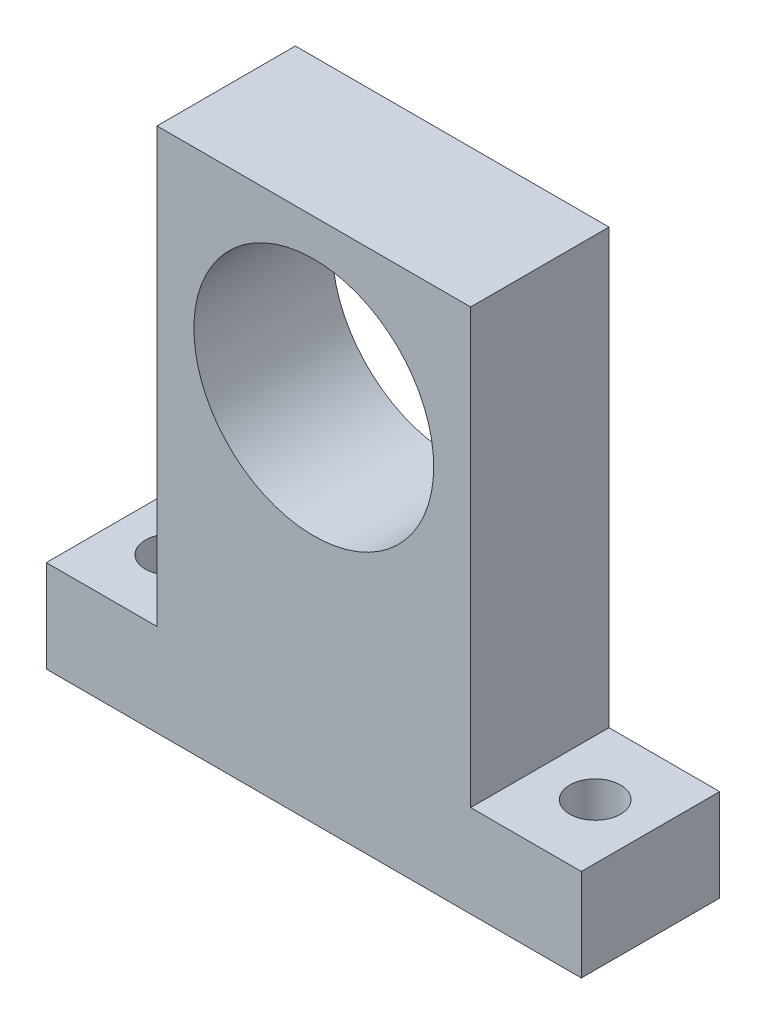
SolidWorks part; units mm, degrees
ref_plane "前视基准面" through (0, 0, 0) normal (0, 0, 1) x (1, 0, 0)
ref_plane "上视基准面" through (0, 0, 0) normal (0, 1, 0) x (1, 0, 0)
ref_plane "右视基准面" through (0, 0, 0) normal (1, 0, 0) x (0, 0, -1)
other "Configuration Table"
sketch "草图1" plane through (0, 0, 0) normal (0, 0, 1) x (1, 0, 0)
  line L0 (0, 0) -> (0, 45542.391) construction
  line L1 (17, 0) -> (-17, 0)
  line L2 (-17, 0) -> (-17, -47)
  line L3 (-17, -47) -> (-29, -47)
  line L4 (-29, -47) -> (-29, -57)
  line L5 (-29, -57) -> (29, -57)
  line L6 (29, -47) -> (29, -57)
  line L7 (17, -47) -> (29, -47)
  line L8 (17, 0) -> (17, -47)
  circle A0 centre (0, -17) radius 13
  point P10 (0, -57)
  point P13 (0, 0)
  dimension "D5" = 26
  dimension "D6" = 40
  dimension "D1" = 58
  dimension "D2" = 34
  dimension "D3" = 10
  dimension "D4" = 57
extrude "凸台-拉伸1" add sketch "草图1" along normal blind 15
sketch "草图2" plane through (0, -47, 0) normal (0, 1, 0) x (1, 0, 0)
  line L0 (-29, -15) -> (-29, 0) construction
  line L1 (0, 0) -> (0, -15) construction
  line L2 (17, -15) -> (-17, -15) construction
  circle A0 centre (-23, -7.5) radius 2.75
  circle A1 centre (23, -7.5) radius 2.75
  point P4 (-29, -7.5)
  dimension "D1" = 5.5
  dimension "D2" = 46
extrude "切除-拉伸1" cut sketch "草图2" against normal through all
